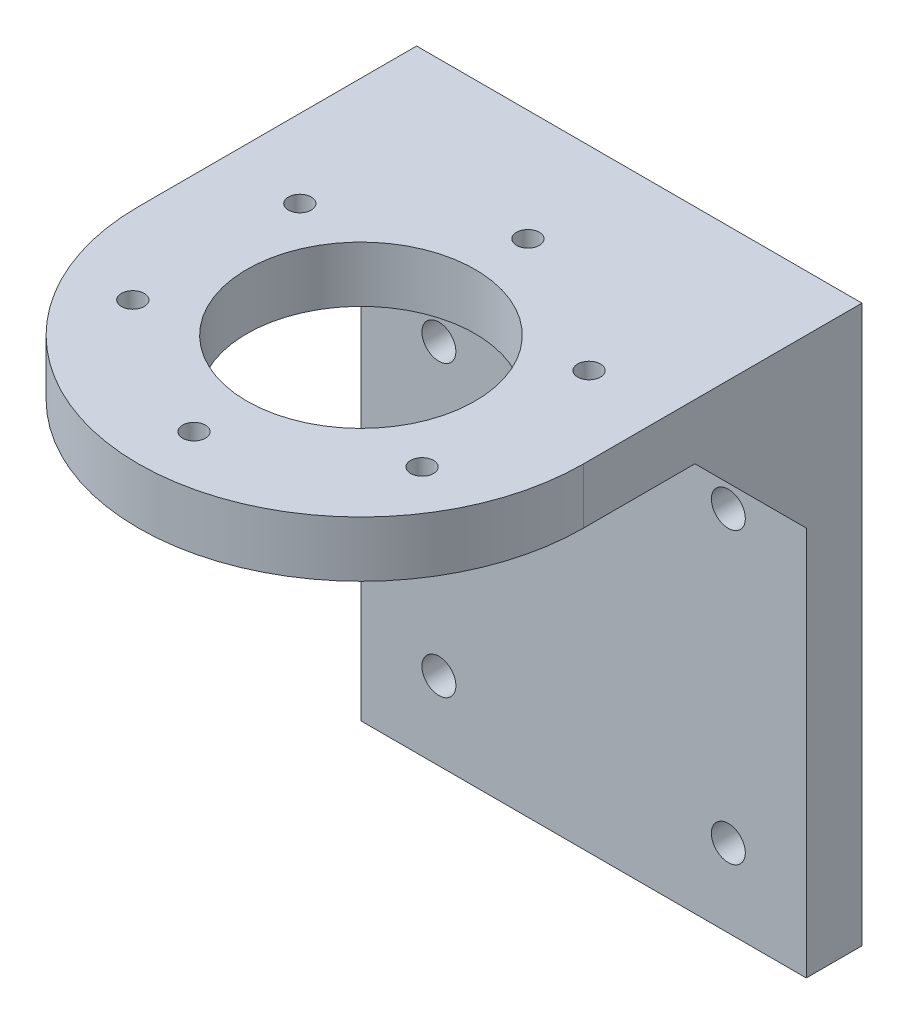
SolidWorks part; units mm, degrees
ref_plane "前视基准面" through (0, 0, 0) normal (0, 0, 1) x (1, 0, 0)
ref_plane "上视基准面" through (0, 0, 0) normal (0, 1, 0) x (1, 0, 0)
ref_plane "右视基准面" through (0, 0, 0) normal (1, 0, 0) x (0, 0, -1)
sketch "草图1" plane through (0, 0, 0) normal (0, 1, 0) x (1, 0, 0)
  line L0 (0, 20) -> (40, 20) construction
  line L1 (0, 0) -> (40, 0)
  line L2 (0, 0) -> (0, 40)
  line L3 (0, 40) -> (40, 40)
  line L4 (40, 0) -> (40, 40)
  line L5 (20, 40) -> (20, 20) construction
  line L6 (20, 20) -> (7.0096, 27.5) construction
  circle A0 centre (7.0096, 27.5) radius 1.025
  circle A1 centre (32.9904, 27.5) radius 1.025
  circle A2 centre (20, 5) radius 1.025
  arc A3 (0, 20) -> (20, 0) centre (20, 20) ccw
  arc A4 (40, 20) -> (20, 0) centre (20, 20) cw
  circle A5 centre (20, 20) radius 10.25
  circle A6 centre (32.9904, 12.5) radius 1.025
  circle A7 centre (7.0096, 12.5) radius 1.025
  circle A8 centre (20, 35) radius 1.025
  point P13 (20, 20)
  dimension "D1" = 2.05
  dimension "D7" = 20.5
  dimension "D3" = 15
  dimension "D4" = 15
  dimension "D5" = 40
  dimension "D6" = 40
  dimension "D2" = 3
extrude "凸台-拉伸2" add sketch "草图1" along normal blind 5 contours A4 L4 L3 L2 A3 A2 A1 A0
ref_plane "基准面1" through (0, 5, 0) normal (0, 1, 0) x (1, 0, 0)
sketch "草图2" plane through (0, 5, 0) normal (0, 1, 0) x (1, 0, 0)
  line L0 (0, 40) -> (40, 40)
  line L1 (0, 40) -> (0, 45)
  line L2 (40, 40) -> (40, 45)
  line L3 (0, 45) -> (40, 45)
  dimension "D1" = 5
extrude "凸台-拉伸3" add sketch "草图2" against normal blind 50
ref_plane "基准面2" through (0, 0, -45) normal (0, 0, -1) x (-1, 0, 0)
sketch "草图3" plane through (0, 0, -45) normal (0, 0, -1) x (-1, 0, 0)
  line L0 (-40, -20) -> (0, -20) construction
  line L1 (-40, -45) -> (-40, 5) construction
  line L2 (0, -45) -> (0, 5) construction
  line L3 (0, -20) -> (-20, -20) construction
  line L4 (-20, -20) -> (-20, 5) construction
  line L5 (22, 5) -> (-22, 5) construction
  line L6 (-20, -25) -> (-7, -12) construction
  circle A0 centre (-7, -12) radius 1.525
  circle A1 centre (-7, -38) radius 1.525
  circle A2 centre (-33, -38) radius 1.525
  circle A3 centre (-33, -12) radius 1.525
  dimension "D3" = 3.05
  dimension "D2" = 26
  dimension "D4" = 26
  dimension "D5" = 13
  dimension "D6" = 5
  dimension "D1" = 4
extrude "切除-拉伸1" cut sketch "草图3" against normal up to next
ref_plane "基准面3" through (0, 0, 0) normal (-1, 0, 0) x (0, 0, 1)
sketch "草图4" plane through (0, 0, 0) normal (-1, 0, 0) x (0, 0, 1)
  line L0 (-30, 0) -> (-40, 0)
  line L1 (-20, 0) -> (-40, 0) construction
  line L2 (-40, 0) -> (-40, -10)
  line L3 (-40, -45) -> (-40, 0) construction
  line L4 (-40, -10) -> (-30, 0)
  dimension "D1" = 10
extrude "凸台-拉伸4" add sketch "草图4" against normal blind 3
ref_plane "基准面4" through (40, 0, 0) normal (1, 0, 0) x (0, 0, -1)
sketch "草图5" plane through (40, 0, 0) normal (1, 0, 0) x (0, 0, -1)
  line L0 (40, -10) -> (40, 0)
  line L1 (40, 0) -> (30, 0)
  line L2 (20, 0) -> (40, 0) construction
  line L3 (30, 0) -> (40, -10)
extrude "凸台-拉伸5" add sketch "草图5" against normal blind 3
